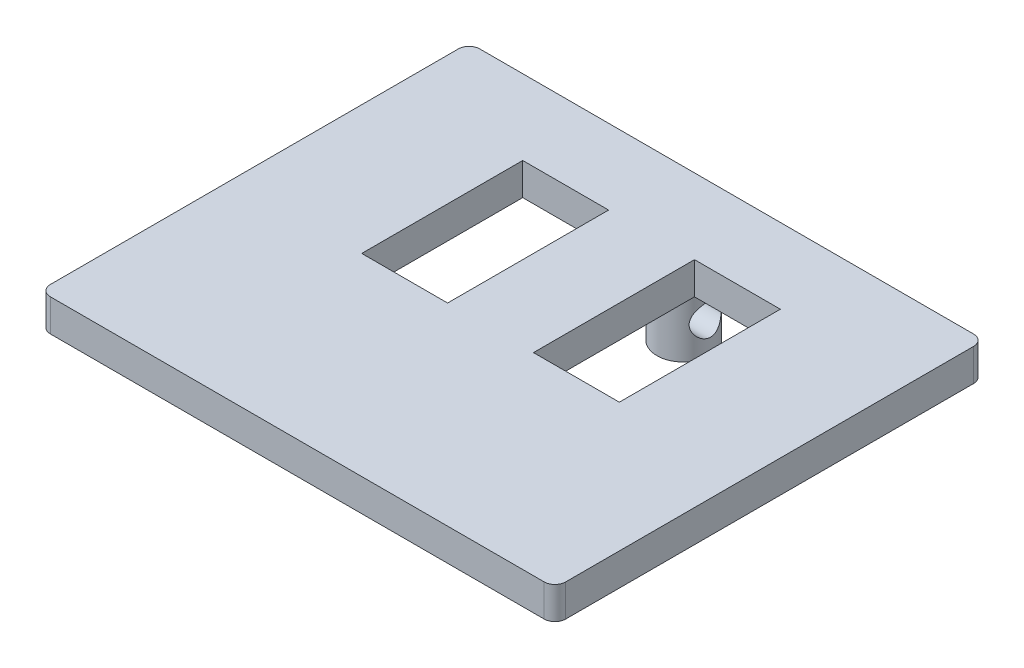
SolidWorks part; units mm, degrees
material "1023 Carbon Steel Sheet (SS)"
ref_plane "Front Plane" through (0, 0, 0) normal (0, 0, 1) x (1, 0, 0)
ref_plane "Top Plane" through (0, 0, 0) normal (0, 1, 0) x (1, 0, 0)
ref_plane "Right Plane" through (0, 0, 0) normal (1, 0, 0) x (0, 0, -1)
sketch "Sketch1" plane through (0, 0, 0) normal (0, 1, 0) x (1, 0, 0)
  line L0 (-4, 13) -> (-12, 13)
  line L1 (-23, -20) -> (23, -20)
  line L2 (-24, -19) -> (-24, 19)
  line L3 (-23, 20) -> (23, 20)
  line L4 (24, -19) -> (24, 19)
  line L5 (-24, -20) -> (24, 20) construction
  line L6 (-24, 20) -> (24, -20) construction
  line L7 (12, -2) -> (4, -2)
  line L8 (12, -2) -> (12, 13)
  line L9 (12, 13) -> (4, 13)
  line L10 (-12, -2) -> (-12, 13)
  line L11 (12, -2) -> (-12, 13) construction
  line L12 (12, 13) -> (-12, -2) construction
  line L13 (-4, -2) -> (-12, -2)
  line L14 (-4, 13) -> (-4, -2)
  line L16 (4, 13) -> (4, -2)
  line L17 (-4, 13) -> (4, -2) construction
  line L18 (-4, -2) -> (4, 13) construction
  arc A0 (-24, 19) -> (-23, 20) centre (-23, 19) cw
  arc A1 (23, 20) -> (24, 19) centre (23, 19) cw
  arc A2 (24, -19) -> (23, -20) centre (23, -19) cw
  arc A3 (-23, -20) -> (-24, -19) centre (-23, -19) cw
  point P0 (0, 0)
  point P6 (0, 5.5)
  point P11 (0, 5.5)
  dimension "D7" = 1
  dimension "D1" = 48
  dimension "D2" = 40
  dimension "D3" = 22
  dimension "D4" = 24
  dimension "D5" = 15
  dimension "D6" = 8
extrude "Boss-Extrude1" add sketch "Sketch1" along normal blind 3
sketch "Sketch2" plane through (0, 0, 0) normal (0, -1, 0) x (1, 0, 0)
  line L0 (23, -20) -> (-23, -20) construction
  circle A0 centre (0, -16) radius 2.5
  point P2 (0, -20)
  dimension "D1" = 5
  dimension "D2" = 4
extrude "Boss-Extrude2" add sketch "Sketch2" along normal blind 7
sketch "Sketch3" plane through (0, 0, 0) normal (-1, 0, 0) x (0, 0, 1)
  line L0 (-19, 0) -> (19, 0) construction
  line L1 (-19.6489, -4) -> (-12.3511, -4) construction
  line L3 (-20, 3) -> (-20, 0) construction
  circle A0 centre (-16, -4) radius 1.5
  dimension "D2" = 3
  dimension "D1" = 4
  dimension "D3" = 4
extrude "Cut-Extrude1" cut sketch "Sketch3" against normal blind 10 and the other way blind 8
